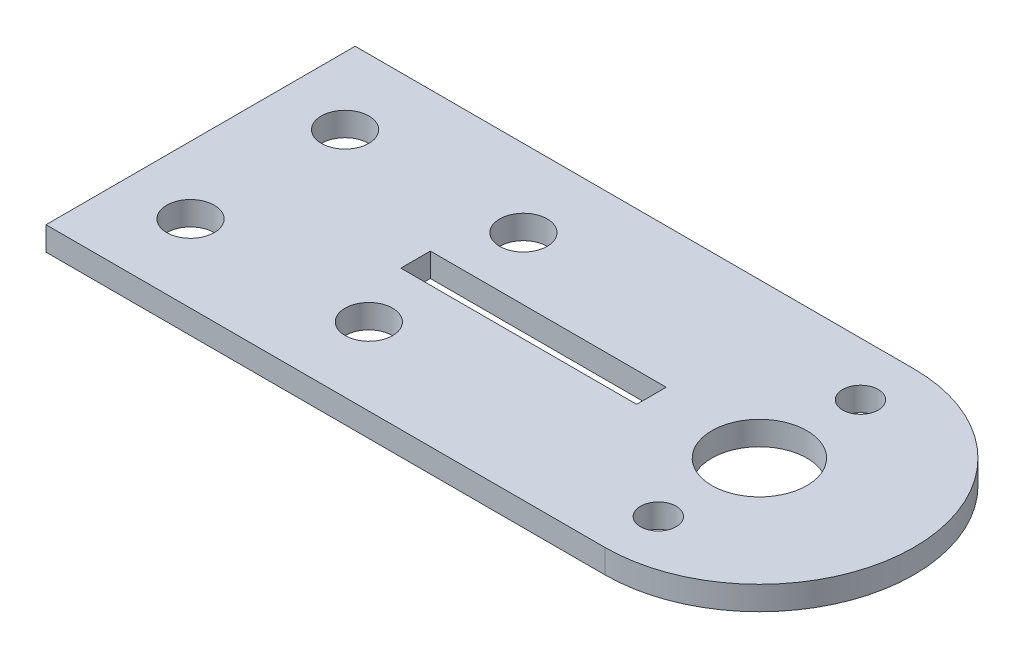
SolidWorks part; units mm, degrees
ref_plane "Front Plane" through (0, 0, 0) normal (0, 0, 1) x (1, 0, 0)
ref_plane "Top Plane" through (0, 0, 0) normal (0, 1, 0) x (1, 0, 0)
ref_plane "Right Plane" through (0, 0, 0) normal (1, 0, 0) x (0, 0, -1)
sketch "Sketch1" plane through (0, 0, 0) normal (0, 1, 0) x (1, 0, 0)
  line L0 (30, 0) -> (17, 0) construction
  line L1 (-30, -13) -> (30, -13) construction
  line L2 (-30, -13) -> (-30, 13) construction
  line L3 (-30, 13) -> (30, 13) construction
  line L4 (30, -13) -> (30, 13) construction
  line L5 (-30, -13) -> (30, 13) construction
  line L6 (-30, 13) -> (30, -13) construction
  line L7 (17, 8.5) -> (17, -8.5) construction
  line L8 (17, 10) -> (17, -10) construction
  circle A0 centre (17, 8.5) radius 1.5
  circle A1 centre (17, -8.5) radius 1.5
  circle A2 centre (17, 0) radius 4
  point P0 (0, 0)
  point P11 (17, 0)
  dimension "D4" = 3
  dimension "D5" = 20
  dimension "D6" = 8
  dimension "D1" = 60
  dimension "D2" = 26
  dimension "D3" = 13
sketch "Sketch2" plane through (0, 0, 0) normal (0, 1, 0) x (1, 0, 0)
  line L0 (17, 8.5) -> (17, 13) construction
  line L1 (-2, -10) -> (-2, -3) construction
  line L2 (-30, 13) -> (30, 13) construction
  line L3 (17, -8.5) -> (17, -13) construction
  line L4 (-30, -13) -> (30, -13) construction
  line L5 (17, -13) -> (-30, -13) construction
  line L6 (-30, -13) -> (-30, 13) construction
  line L7 (-30, 13) -> (17, 13) construction
  line L8 (30, 0) -> (-2, 0) construction
  line L9 (-2, 10) -> (-2, -10) construction
  line L10 (-2, -10) -> (-26.1674, -10) construction
  line L11 (-26.1674, -10) -> (-26.1674, 10) construction
  line L12 (-26.1674, 10) -> (-2, 10) construction
  line L13 (-2, 10) -> (-2, 3) construction
  line L14 (-2, 6.5) -> (-26.1674, 6.5) construction
  line L15 (-2, -6.5) -> (-26.1674, -6.5) construction
  line L16 (-24.3465, 6.5) -> (-24.3465, -6.5) construction
  line L17 (-9.3465, 6.5) -> (-9.3465, -6.5) construction
  arc A0 (17, 13) -> (17, -13) centre (17, 0) cw
  circle A1 centre (-24.3465, -6.5) radius 2
  circle A2 centre (-9.3465, -6.5) radius 2
  circle A3 centre (-24.3465, 6.5) radius 2
  circle A4 centre (-9.3465, 6.5) radius 2
  point P23 (-2, 0)
  dimension "D7" = 4
  dimension "D1" = 32
  dimension "D2" = 20
  dimension "D3" = 7
  dimension "D4" = 7
  dimension "D5" = 3.5
  dimension "D6" = 3.5
  dimension "D8" = 15
sketch "Sketch3" plane through (0, 0, 0) normal (0, 1, 0) x (1, 0, 0)
  line L0 (17, 13) -> (-30, 13)
  line L1 (-30, 13) -> (-30, -13)
  line L2 (-30, -13) -> (17, -13)
  arc A0 (17, -13) -> (17, 13) centre (17, 0) ccw construction
  arc A1 (17, -13) -> (17, 13) centre (17, 0) ccw
  circle A2 centre (-24.3465, -6.5) radius 2 construction
  circle A3 centre (-9.3465, -6.5) radius 2 construction
  circle A4 centre (-9.3465, 6.5) radius 2 construction
  circle A5 centre (-24.3465, 6.5) radius 2 construction
  circle A6 centre (-24.3465, -6.5) radius 2
  circle A7 centre (-9.3465, -6.5) radius 2
  circle A8 centre (-9.3465, 6.5) radius 2
  circle A9 centre (-24.3465, 6.5) radius 2
  circle A10 centre (17, -8.5) radius 1.5 construction
  circle A11 centre (17, 8.5) radius 1.5 construction
  circle A12 centre (17, -8.5) radius 1.5
  circle A13 centre (17, 8.5) radius 1.5
  circle A14 centre (17, 0) radius 4 construction
  circle A15 centre (17, 0) radius 4
extrude "Boss-Extrude1" add sketch "Sketch3" along normal blind 2
sketch "Sketch5" plane through (0, 2, 0) normal (0, 1, 0) x (1, 0, 0)
  line L0 (-30, 0) -> (-17.4509, 0) construction
  line L1 (-30, -13) -> (-30, 13) construction
  circle A0 centre (-17.4509, 0) radius 1.7193 construction
sketch "Sketch6" plane through (0, 2, 0) normal (0, 1, 0) x (1, 0, 0)
  line L1 (-11.9193, -1.244) -> (7.9193, -1.244)
  line L2 (-11.9193, -1.244) -> (-11.9193, 1.244)
  line L3 (-11.9193, 1.244) -> (7.9193, 1.244)
  line L4 (7.9193, -1.244) -> (7.9193, 1.244)
  line L5 (-11.9193, -1.244) -> (7.9193, 1.244) construction
  line L6 (-11.9193, 1.244) -> (7.9193, -1.244) construction
  point P0 (-2, 0)
extrude "Cut-Extrude1" cut sketch "Sketch6" against normal blind 50
